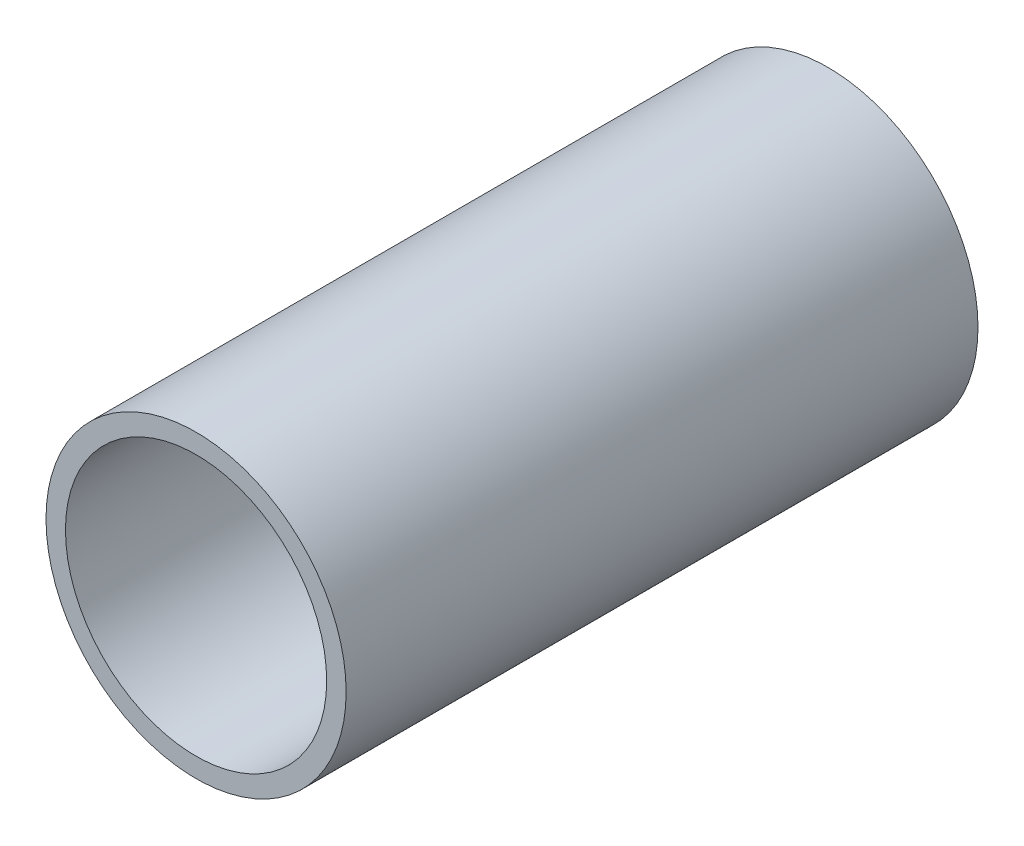
SolidWorks part; units mm, degrees
ref_plane "Front Plane" through (0, 0, 0) normal (0, 0, 1) x (1, 0, 0)
ref_plane "Top Plane" through (0, 0, 0) normal (0, 1, 0) x (1, 0, 0)
ref_plane "Right Plane" through (0, 0, 0) normal (1, 0, 0) x (0, 0, -1)
sketch "Sketch1" plane through (0, 0, 0) normal (0, 0, 1) x (1, 0, 0)
  circle A0 centre (0, 0) radius 30.1625
  circle A1 centre (0, 0) radius 26.2509
  dimension "D1" = 60.325
  dimension "D2" = 3.9116
extrude "Boss-Extrude1" add sketch "Sketch1" along normal blind 127
